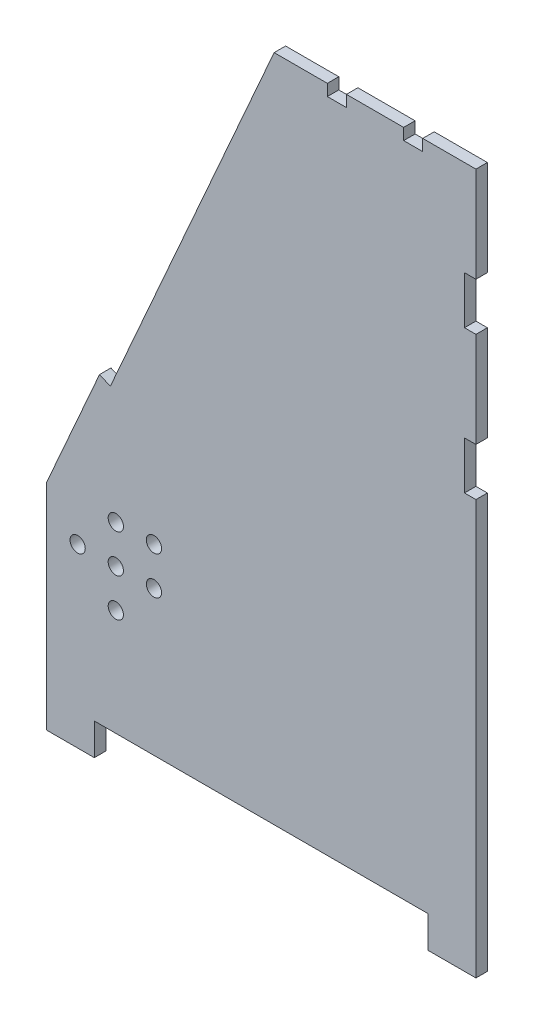
SolidWorks part; units mm, degrees
ref_plane "Front Plane" through (0, 0, 0) normal (0, 0, 1) x (1, 0, 0)
ref_plane "Top Plane" through (0, 0, 0) normal (0, 1, 0) x (1, 0, 0)
ref_plane "Right Plane" through (0, 0, 0) normal (1, 0, 0) x (0, 0, -1)
sketch "Sketch1" plane through (0, 0, 0) normal (0, 0, 1) x (1, 0, 0)
  line L0 (0, 0) -> (-45, 0)
  line L1 (45, 30) -> (-45, 30)
  line L2 (45, 30) -> (45, -30)
  line L3 (45, -30) -> (-45, -30)
  line L4 (-45, 30) -> (-45, -30)
  line L5 (45, 30) -> (-45, -30) construction
  line L6 (45, -30) -> (-45, 30) construction
  line L7 (-22.5, 0) -> (-22.5, 15)
  line L8 (-45, 30) -> (-45, 15)
  line L9 (-45, 15) -> (-34.3476, 39.1134)
  line L10 (2.7, 116.8645) -> (45, 116.8645)
  line L11 (45, 116.8645) -> (45, 30)
  line L12 (-45, -30) -> (-35, -30)
  line L13 (-35, -30) -> (-35, -23.3333)
  line L14 (-35, -23.3333) -> (35, -23.3333)
  line L15 (35, -23.3333) -> (35, -30)
  line L19 (2.7, 116.8645) -> (-31.6476, 39.1134)
  line L20 (23.85, 116.8645) -> (17.85, 116.8645)
  line L21 (17.85, 116.8645) -> (17.85, 114.4645)
  line L22 (17.85, 114.4645) -> (13.85, 114.4645)
  line L23 (13.85, 114.4645) -> (13.85, 116.8645)
  line L24 (23.85, 116.8645) -> (23.85, 30)
  line L25 (29.85, 116.8645) -> (29.85, 114.4645)
  line L26 (29.85, 114.4645) -> (33.85, 114.4645)
  line L27 (33.85, 114.4645) -> (33.85, 116.8645)
  line L28 (45, 116.8645) -> (45, 96.8645)
  line L29 (45, 96.8645) -> (42.6, 96.8645)
  line L30 (42.6, 96.8645) -> (42.6, 86.8645)
  line L31 (42.6, 86.8645) -> (45, 86.8645)
  line L32 (45, 86.8645) -> (45, 66.8645)
  line L33 (45, 66.8645) -> (42.6, 66.8645)
  line L34 (42.6, 66.8645) -> (42.6, 56.8645)
  line L35 (42.6, 56.8645) -> (45, 56.8645)
  line L36 (45, 56.8645) -> (45, 30)
  line L37 (-35.4026, 36.7253) -> (-33.9067, 40.1114)
  line L38 (-31.6476, 39.1134) -> (-33.9067, 40.1114)
  line L39 (-22.5, 15) -> (-30.5, 15)
  line L41 (-22.5, 15) -> (-30.5, 15)
  line L42 (-22.5, 15) -> (-22.5, 7)
  line L43 (-22.5, 7) -> (-30.5, 7)
  line L44 (-30.5, 15) -> (-30.5, 7)
  line L45 (-30.5, 7) -> (-38.5, 7)
  line L46 (-30.5, 7) -> (-30.5, -1)
  line L47 (-30.5, -1) -> (-38.5, -1)
  line L48 (-38.5, 7) -> (-38.5, -1)
  circle A0 centre (-22.5, 15) radius 1.6
  circle A1 centre (-30.5, 15) radius 1.6
  circle A2 centre (-30.5, 7) radius 1.6
  circle A3 centre (-22.5, 7) radius 1.6
  circle A4 centre (-38.5, 7) radius 1.6
  circle A5 centre (-30.5, -1) radius 1.6
  point P0 (0, 0)
extrude "Boss-Extrude1" add sketch "Sketch1" along normal blind 2.4
